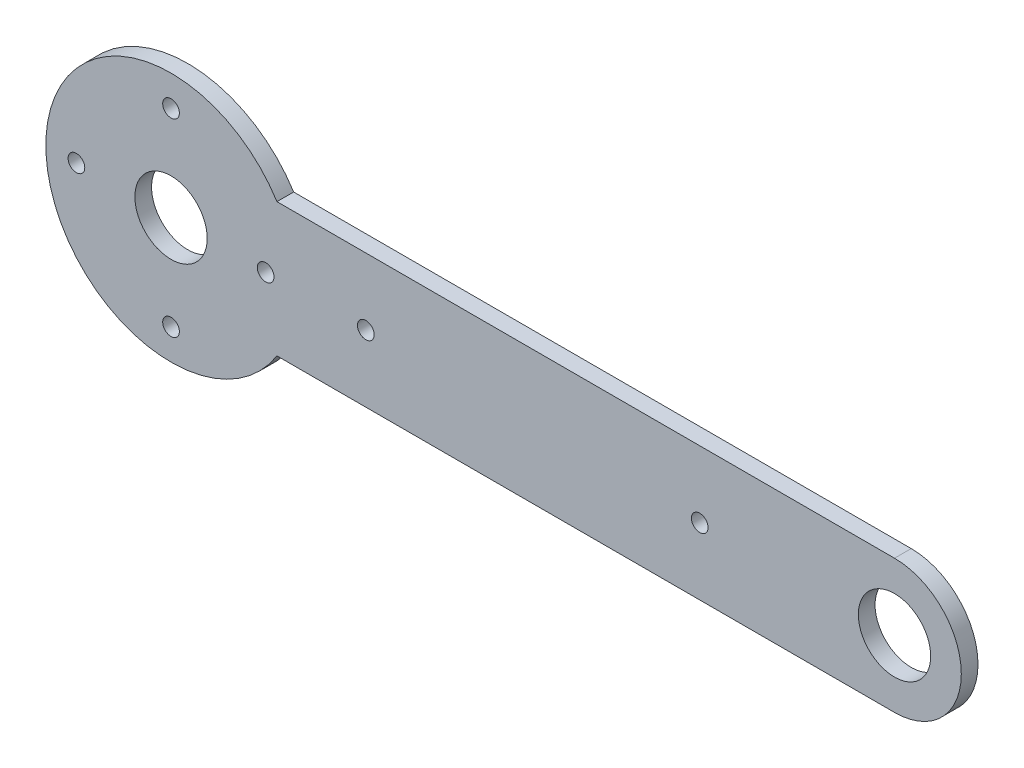
SolidWorks part; units mm, degrees
ref_plane "Plan de face" through (0, 0, 0) normal (0, 0, 1) x (1, 0, 0)
ref_plane "Plan de dessus" through (0, 0, 0) normal (0, 1, 0) x (1, 0, 0)
ref_plane "Plan de droite" through (0, 0, 0) normal (1, 0, 0) x (0, 0, -1)
sketch "Esquisse1" plane through (0, 0, 0) normal (0, 0, 1) x (1, 0, 0)
  line L0 (-79.2886, 0) -> (141.1723, 0) construction
  line L1 (0, 65.9449) -> (0, -87.2174) construction
  line L3 (-65, 12) -> (65, 12)
  line L5 (-65, -12) -> (65, -12)
  arc A0 (-65, 12) -> (-65, -12) centre (-65, 0) ccw
  arc A1 (65, 12) -> (65, -12) centre (65, 0) cw
  dimension "D2" = 12
  dimension "D1" = 130
extrude "Boss.-Extru.1" add sketch "Esquisse1" along normal blind 3
sketch "Esquisse2" plane through (0, 0, 3) normal (0, 0, 1) x (1, 0, 0)
  line L0 (0, 32.5631) -> (0, -50.0545) construction
  line L1 (0, 0) -> (-119.9738, 0) construction
  circle A0 centre (-65, 0) radius 6.5
  circle A1 centre (65, 0) radius 6.5
  arc A2 (-65, 12) -> (-65, -12) centre (-65, 0) ccw construction
  arc A3 (-65, 12) -> (-65, -12) centre (-65, 0) ccw construction
  point P10 (-77, 0)
  dimension "D1" = 13
  dimension "D2" = 12
extrude "Enlèv. mat.-Extru.1" cut sketch "Esquisse2" against normal through all
sketch "Esquisse4" plane through (0, 0, 3) normal (0, 0, 1) x (1, 0, 0)
  line L0 (0, 20.3403) -> (0, -18.9277) construction
  line L1 (-96.5346, 0) -> (87.2423, 0) construction
  circle A0 centre (-30, 0) radius 1.5
  circle A1 centre (30, 0) radius 1.5
  dimension "D1" = 3
  dimension "D2" = 60
extrude "Enlèv. mat.-Extru.2" cut sketch "Esquisse4" against normal through all both contours A0 | A1
sketch "Esquisse5" plane through (0, 0, 3) normal (0, 0, 1) x (1, 0, 0)
  circle A0 centre (-65, 0) radius 22.5
  circle A1 centre (-65, 0) radius 6.5
  dimension "D1" = 45
extrude "Boss.-Extru.2" add sketch "Esquisse5" against normal blind 3
sketch "Esquisse6" plane through (0, 0, 3) normal (0, 0, 1) x (1, 0, 0)
  circle A0 centre (-65, 0) radius 17 construction
  circle A1 centre (-65, 17) radius 1.5
  circle A2 centre (-48, 0) radius 1.5
  circle A3 centre (-65, 0) radius 17 construction
  circle A4 centre (-65, -17) radius 1.5
  circle A5 centre (-65, 0) radius 17 construction
  circle A6 centre (-82, 0) radius 1.5
  circle A7 centre (-65, 0) radius 17 construction
  point P17 (-65, 0)
  dimension "D1" = 3
  dimension "D2" = 17
  dimension "D3" = 4
extrude "Enlèv. mat.-Extru.3" cut sketch "Esquisse6" against normal through all
